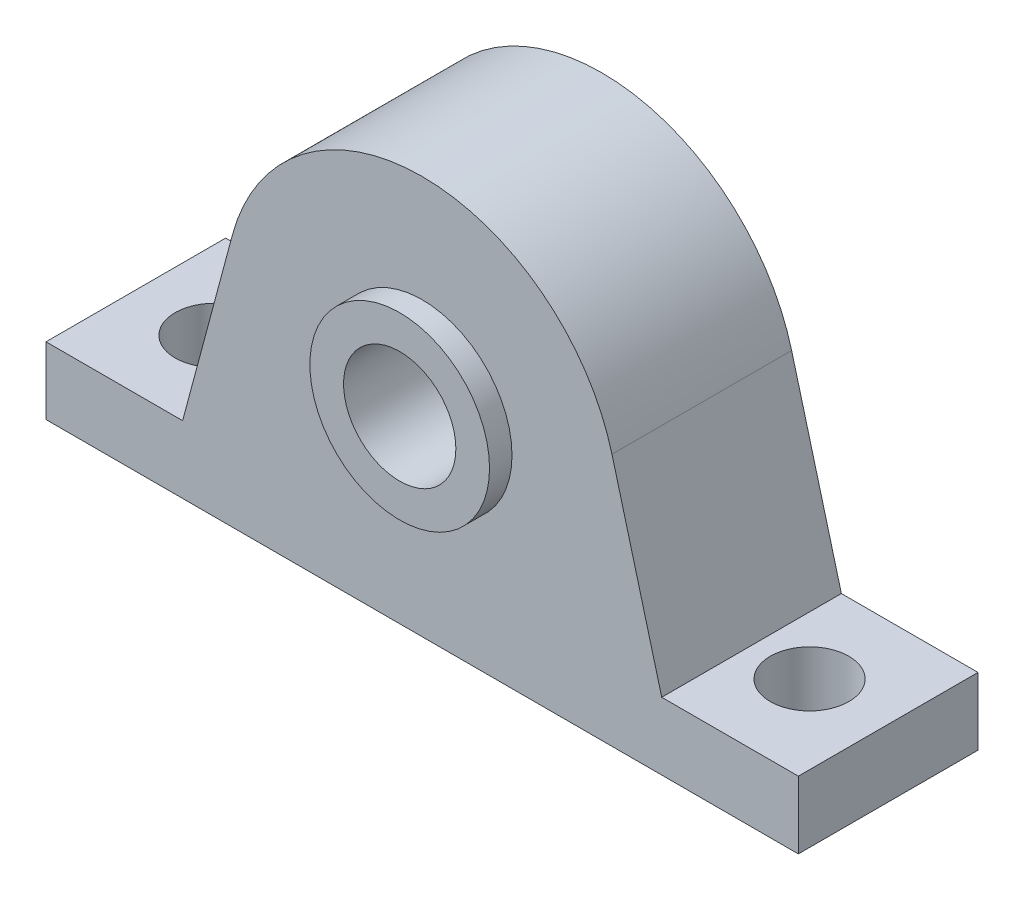
SolidWorks part; units mm, degrees
ref_plane "前视基准面" through (0, 0, 0) normal (0, 0, 1) x (1, 0, 0)
ref_plane "上视基准面" through (0, 0, 0) normal (0, 1, 0) x (1, 0, 0)
ref_plane "右视基准面" through (0, 0, 0) normal (1, 0, 0) x (0, 0, -1)
sketch "草图1" plane through (0, 0, 0) normal (0, 0, 1) x (1, 0, 0)
  line L0 (-33.1707, 0) -> (31.7073, 0) construction
  line L1 (0, 28.7317) -> (0, -23.1707) construction
  line L2 (-33.5, 0) -> (-33.5, 6)
  line L3 (-33.5, 6) -> (-21.3327, 6)
  line L4 (-33.5, 0) -> (33.5, 0)
  line L5 (-21.3327, 6) -> (-16.9037, 22.5293)
  line L6 (33.5, 0) -> (33.5, 6)
  line L7 (21.3327, 6) -> (16.9037, 22.5293)
  line L8 (33.5, 6) -> (21.3327, 6)
  circle A0 centre (0, 18) radius 17.5
  circle A1 centre (0, 18) radius 5
  point P13 (0, 0)
  dimension "D2" = 10
  dimension "D5" = 35
  dimension "D1" = 18
  dimension "D3" = 6
  dimension "D4" = 67
  dimension "D6" = 75
extrude "凸台-拉伸1" add sketch "草图1" along normal blind 16 contours A0 L5 L3 L2 L4 L6 L8 L7 | A0 A1
sketch "草图2" plane through (0, 0, 16) normal (0, 0, 1) x (1, 0, 0)
  circle A0 centre (0, 18) radius 8
  circle A1 centre (0, 18) radius 5 construction
  circle A2 centre (0, 18) radius 5
  dimension "D1" = 16
extrude "凸台-拉伸2" add sketch "草图2" along normal blind 2
sketch "草图3" plane through (0, 6, 0) normal (0, 1, 0) x (1, 0, 0)
  line L0 (-33.5, -8) -> (33.5, -8) construction
  line L1 (-33.5, -16) -> (-33.5, 0) construction
  line L2 (33.5, -16) -> (33.5, 0) construction
  line L3 (0, 0) -> (0, -36.7743) construction
  circle A0 centre (-26.5, -8) radius 3.5
  circle A1 centre (26.5, -8) radius 3.5
  dimension "D1" = 7
  dimension "D2" = 53
extrude "切除-拉伸1" cut sketch "草图3" against normal blind 12
